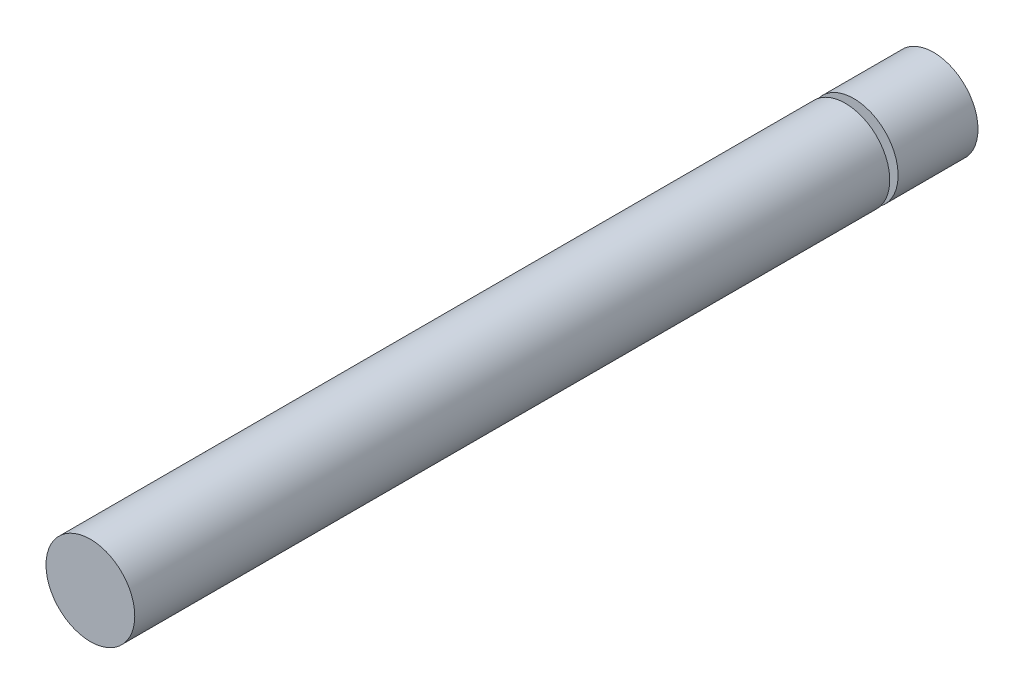
SolidWorks part; units mm, degrees
ref_plane "Front Plane" through (0, 0, 0) normal (0, 0, 1) x (1, 0, 0)
ref_plane "Top Plane" through (0, 0, 0) normal (0, 1, 0) x (1, 0, 0)
ref_plane "Right Plane" through (0, 0, 0) normal (1, 0, 0) x (0, 0, -1)
sketch "Sketch1" plane through (0, 0, 0) normal (0, 0, 1) x (1, 0, 0)
  circle A0 centre (0, 0) radius 5
  dimension "D1" = 10
extrude "Boss-Extrude1" add sketch "Sketch1" along normal mid plane 95
sketch "Sketch2" plane through (0, 0, 0) normal (0, 1, 0) x (1, 0, 0)
  line L0 (-5, 47.5) -> (-5, -47.5) construction
  line L1 (-5, 37.56) -> (-3.5, 37.56)
  line L3 (-5, 38.5) -> (-3.5, 38.5)
  line L4 (-3.5, 37.56) -> (-3.5, 38.5)
  line L5 (-5, 37.56) -> (-5, 47.5) construction
  line L6 (-5, 38.5) -> (-5, 47.5) construction
  line L7 (0, -5.5) -> (0, 5.5) construction
  line L8 (-5, 37.56) -> (-5, 38.5)
  line L9 (0, 47.5) -> (0, -47.5) construction
  line L10 (5, 47.5) -> (-5, 47.5) construction
  line L11 (-5, -47.5) -> (5, -47.5) construction
  dimension "D1" = 9
  dimension "D2" = 0.94
  dimension "D3" = 3.5
revolve "Cut-Revolve1" cut sketch "Sketch2" angle 360 about L9
